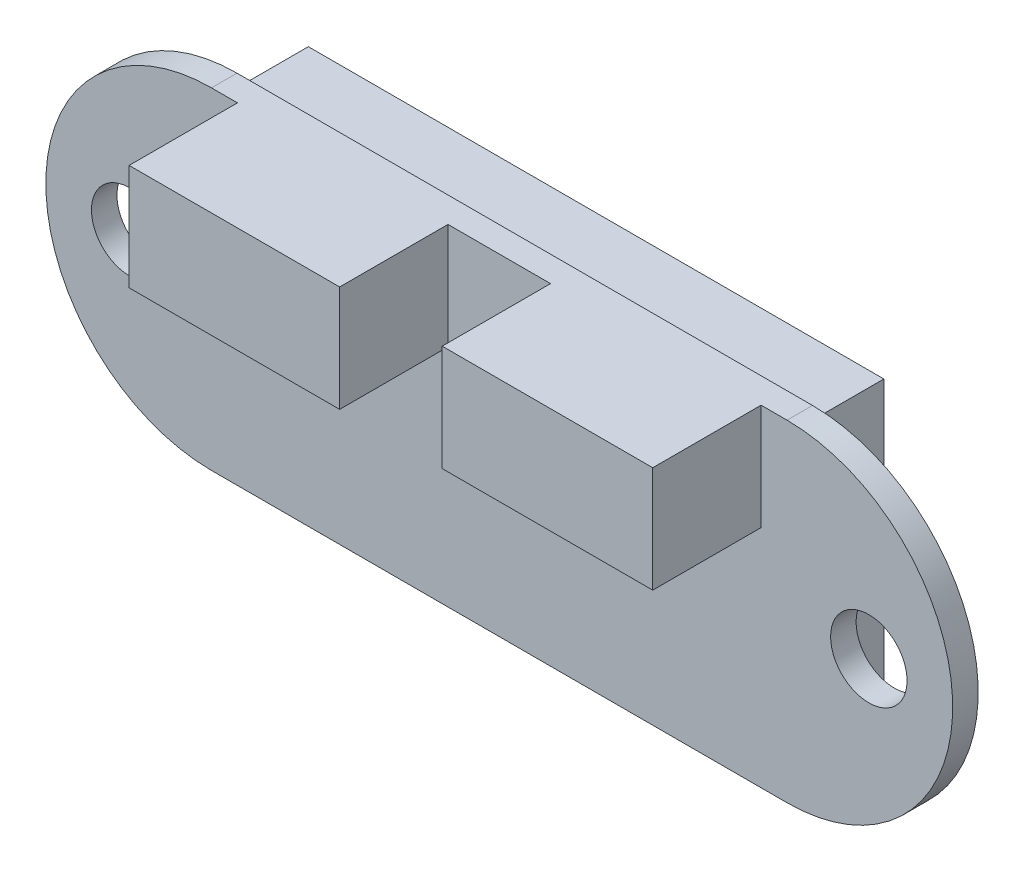
SolidWorks part; units mm, degrees
ref_plane "Front Plane" through (0, 0, 0) normal (0, 0, 1) x (1, 0, 0)
ref_plane "Top Plane" through (0, 0, 0) normal (0, 1, 0) x (1, 0, 0)
ref_plane "Right Plane" through (0, 0, 0) normal (1, 0, 0) x (0, 0, -1)
sketch "Sketch1" plane through (0, 0, 0) normal (0, 0, 1) x (1, 0, 0)
  line L0 (-62.3183, 28.6187) -> (-62.3183, 15.6187) construction
  line L1 (-73.6083, 15.6187) -> (-51.0283, 15.6187)
  line L3 (-73.6083, 28.6187) -> (-51.0283, 28.6187)
  line L5 (-73.6083, 15.6187) -> (-51.0283, 28.6187) construction
  line L6 (-73.6083, 28.6187) -> (-51.0283, 15.6187) construction
  arc A0 (-51.0283, 15.6187) -> (-51.0283, 28.6187) centre (-51.0283, 22.1187) ccw
  arc A1 (-73.6083, 28.6187) -> (-73.6083, 15.6187) centre (-73.6083, 22.1187) ccw
  circle A2 centre (-76.8183, 22.1187) radius 1.5
  circle A3 centre (-47.8183, 22.1187) radius 1.5
  point P0 (-62.3183, 22.1187)
  dimension "D3" = 3
  dimension "D1" = 22.58
  dimension "D2" = 13
  dimension "D4" = 14.5
extrude "Boss-Extrude1" add sketch "Sketch1" along normal blind 1
sketch "Sketch3" plane through (0, 0, 0) normal (0, 0, -1) x (-1, 0, 0)
  line L0 (62.3183, 15.6187) -> (62.3183, 28.6187) construction
  line L1 (73.6083, 15.6187) -> (51.0283, 15.6187) construction
  line L2 (51.0283, 28.6187) -> (73.6083, 28.6187) construction
  line L4 (73.6083, 28.1187) -> (51.0283, 28.1187)
  line L5 (73.6083, 28.1187) -> (73.6083, 16.1187)
  line L6 (73.6083, 16.1187) -> (51.0283, 16.1187)
  line L7 (51.0283, 28.1187) -> (51.0283, 16.1187)
  line L8 (73.6083, 28.1187) -> (51.0283, 16.1187) construction
  line L9 (73.6083, 16.1187) -> (51.0283, 28.1187) construction
  line L10 (61.09, 24.1187) -> (55.09, 24.1187)
  line L11 (61.09, 24.1187) -> (61.09, 20.1187)
  line L12 (61.09, 20.1187) -> (55.09, 20.1187)
  line L13 (55.09, 24.1187) -> (55.09, 20.1187)
  line L14 (61.09, 24.1187) -> (55.09, 20.1187) construction
  line L15 (61.09, 20.1187) -> (55.09, 24.1187) construction
  point P6 (62.3183, 22.1187)
  point P11 (58.09, 22.1187)
  point P16 (56.3788, 22.1187)
  point P17 (58.09, 22.1187)
  dimension "D1" = 12
  dimension "D2" = 22.58
  dimension "D3" = 6
  dimension "D4" = 4
extrude "Boss-Extrude2" add sketch "Sketch3" along normal blind 2.8
sketch "Sketch4" plane through (0, 0, 1) normal (0, 0, 1) x (1, 0, 0)
  line L0 (-62.3183, 28.6187) -> (-62.3183, 15.6187) construction
  line L1 (-72.5902, 24.4587) -> (-64.3302, 24.4587)
  line L2 (-72.5902, 24.4587) -> (-72.5902, 28.6187)
  line L3 (-72.5902, 28.6187) -> (-64.3302, 28.6187)
  line L4 (-64.3302, 24.4587) -> (-64.3302, 28.6187)
  line L5 (-72.5902, 24.4587) -> (-64.3302, 28.6187) construction
  line L6 (-72.5902, 28.6187) -> (-64.3302, 24.4587) construction
  line L7 (-51.0283, 28.6187) -> (-73.6083, 28.6187) construction
  line L8 (-73.6083, 15.6187) -> (-51.0283, 15.6187) construction
  line L9 (-52.0465, 28.6187) -> (-60.3065, 28.6187)
  line L10 (-60.3065, 24.4587) -> (-60.3065, 28.6187)
  line L11 (-52.0465, 24.4587) -> (-60.3065, 24.4587)
  line L12 (-52.0465, 24.4587) -> (-52.0465, 28.6187)
  point P0 (-68.4602, 26.5387)
  point P15 (-64.3302, 28.6187)
  dimension "D1" = 4.16
  dimension "D2" = 8.26
extrude "Boss-Extrude3" add sketch "Sketch4" along normal blind 4.25
